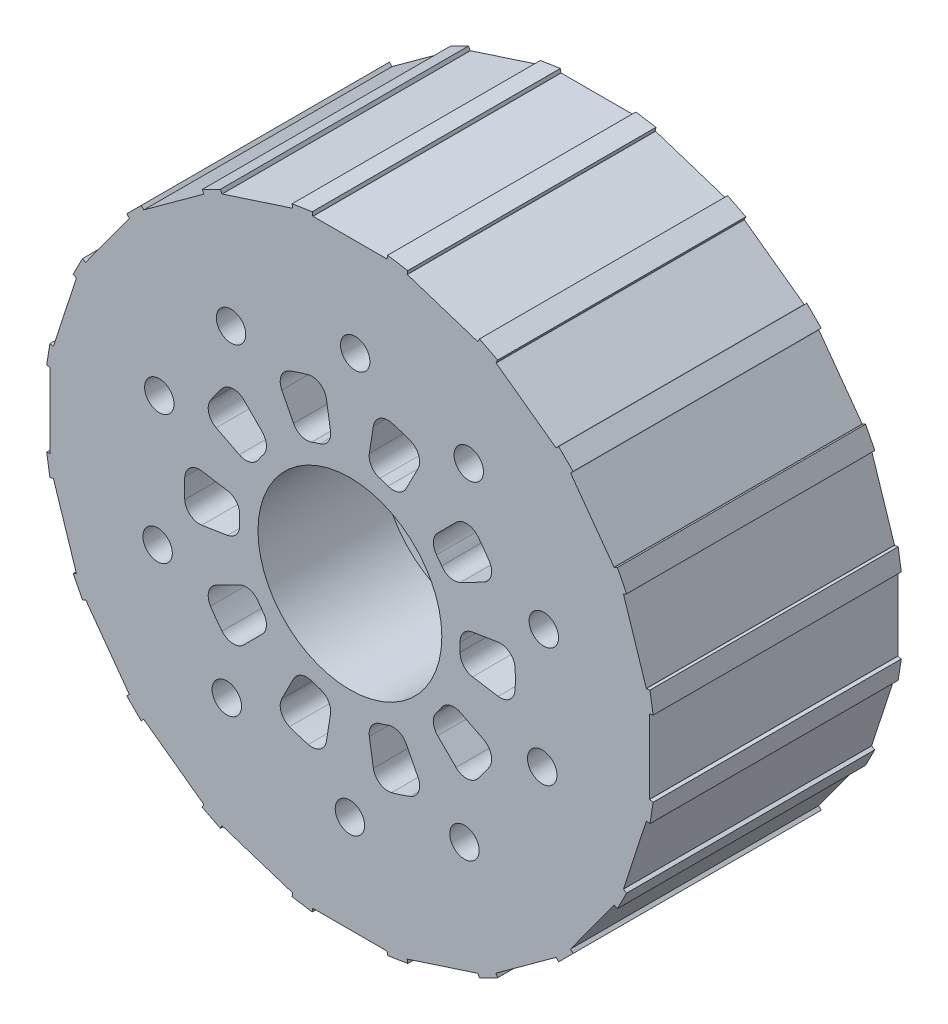
SolidWorks part; units mm, degrees
ref_plane "Ön Düzlem" through (0, 0, 0) normal (0, 0, 1) x (1, 0, 0)
ref_plane "Üst Düzlem" through (0, 0, 0) normal (0, 1, 0) x (1, 0, 0)
ref_plane "Sağ Düzlem" through (0, 0, 0) normal (1, 0, 0) x (0, 0, -1)
sketch "Sketch1" plane through (0, 0, 0) normal (0, 0, 1) x (1, 0, 0)
  line L0 (0, 0) -> (0, 81.5)
  line L1 (10, 81.5) -> (-10, 81.5)
  line L2 (-10, 81.5) -> (-10, 87.5)
  line L3 (10, 81.5) -> (10, 87.5)
  line L4 (15.6743, 80.6013) -> (17.5284, 86.3076)
  line L5 (34.6955, 74.4209) -> (36.5496, 80.1273)
  line L6 (34.6955, 74.4209) -> (15.6743, 80.6013)
  line L7 (39.8143, 71.8127) -> (43.341, 76.6668)
  line L8 (55.9947, 60.057) -> (59.5214, 64.9111)
  line L9 (55.9947, 60.057) -> (39.8143, 71.8127)
  line L10 (60.057, 55.9947) -> (64.9111, 59.5214)
  line L11 (71.8127, 39.8143) -> (76.6668, 43.341)
  line L12 (71.8127, 39.8143) -> (60.057, 55.9947)
  line L13 (74.4209, 34.6955) -> (80.1273, 36.5496)
  line L14 (80.6013, 15.6743) -> (86.3076, 17.5284)
  line L15 (80.6013, 15.6743) -> (74.4209, 34.6955)
  line L16 (81.5, 10) -> (87.5, 10)
  line L17 (81.5, -10) -> (87.5, -10)
  line L18 (81.5, -10) -> (81.5, 10)
  line L19 (80.6013, -15.6743) -> (86.3076, -17.5284)
  line L20 (74.4209, -34.6955) -> (80.1273, -36.5496)
  line L21 (74.4209, -34.6955) -> (80.6013, -15.6743)
  line L22 (71.8127, -39.8143) -> (76.6668, -43.341)
  line L23 (60.057, -55.9947) -> (64.9111, -59.5214)
  line L24 (60.057, -55.9947) -> (71.8127, -39.8143)
  line L25 (55.9947, -60.057) -> (59.5214, -64.9111)
  line L26 (39.8143, -71.8127) -> (43.341, -76.6668)
  line L27 (39.8143, -71.8127) -> (55.9947, -60.057)
  line L28 (34.6955, -74.4209) -> (36.5496, -80.1273)
  line L29 (15.6743, -80.6013) -> (17.5284, -86.3076)
  line L30 (15.6743, -80.6013) -> (34.6955, -74.4209)
  line L31 (10, -81.5) -> (10, -87.5)
  line L32 (-10, -81.5) -> (-10, -87.5)
  line L33 (-10, -81.5) -> (10, -81.5)
  line L34 (-15.6743, -80.6013) -> (-17.5284, -86.3076)
  line L35 (-34.6955, -74.4209) -> (-36.5496, -80.1273)
  line L36 (-34.6955, -74.4209) -> (-15.6743, -80.6013)
  line L37 (-39.8143, -71.8127) -> (-43.341, -76.6668)
  line L38 (-55.9947, -60.057) -> (-59.5214, -64.9111)
  line L39 (-55.9947, -60.057) -> (-39.8143, -71.8127)
  line L40 (-60.057, -55.9947) -> (-64.9111, -59.5214)
  line L41 (-71.8127, -39.8143) -> (-76.6668, -43.341)
  line L42 (-71.8127, -39.8143) -> (-60.057, -55.9947)
  line L43 (-74.4209, -34.6955) -> (-80.1273, -36.5496)
  line L44 (-80.6013, -15.6743) -> (-86.3076, -17.5284)
  line L45 (-80.6013, -15.6743) -> (-74.4209, -34.6955)
  line L46 (-81.5, -10) -> (-87.5, -10)
  line L47 (-81.5, 10) -> (-87.5, 10)
  line L48 (-81.5, 10) -> (-81.5, -10)
  line L49 (-80.6013, 15.6743) -> (-86.3076, 17.5284)
  line L50 (-74.4209, 34.6955) -> (-80.1273, 36.5496)
  line L51 (-74.4209, 34.6955) -> (-80.6013, 15.6743)
  line L52 (-71.8127, 39.8143) -> (-76.6668, 43.341)
  line L53 (-60.057, 55.9947) -> (-64.9111, 59.5214)
  line L54 (-60.057, 55.9947) -> (-71.8127, 39.8143)
  line L55 (-55.9947, 60.057) -> (-59.5214, 64.9111)
  line L56 (-39.8143, 71.8127) -> (-43.341, 76.6668)
  line L57 (-39.8143, 71.8127) -> (-55.9947, 60.057)
  line L58 (-34.6955, 74.4209) -> (-36.5496, 80.1273)
  line L59 (-15.6743, 80.6013) -> (-17.5284, 86.3076)
  line L60 (-15.6743, 80.6013) -> (-34.6955, 74.4209)
  line L61 (34.6955, 74.4209) -> (34.7846, 74.3755)
  line L62 (35.1494, 75.3119) -> (40.2683, 72.7037) construction
  line L63 (39.7252, 71.8581) -> (39.8143, 71.8127)
  line L64 (35.2385, 75.2665) -> (40.1792, 72.7491)
  line L65 (34.7846, 74.3755) -> (35.2385, 75.2665)
  line L66 (55.9947, 60.057) -> (56.0654, 59.9863)
  line L67 (39.7252, 71.8581) -> (40.1792, 72.7491)
  line L68 (34.7846, 74.3755) -> (35.1931, 75.1774) construction
  line L69 (39.7252, 71.8581) -> (40.1338, 72.66) construction
  line L70 (35.1931, 75.1774) -> (40.1338, 72.66) construction
  line L71 (34.6955, 74.4209) -> (35.1494, 75.3119) construction
  line L72 (39.8143, 71.8127) -> (40.2683, 72.7037) construction
  line L73 (56.0654, 59.9863) -> (56.7725, 60.6934)
  line L74 (56.7725, 60.6934) -> (60.6934, 56.7725)
  line L75 (59.9863, 56.0654) -> (60.6934, 56.7725)
  line L76 (59.9863, 56.0654) -> (60.057, 55.9947)
  line L77 (71.8127, 39.8143) -> (71.8581, 39.7252)
  line L78 (71.8581, 39.7252) -> (72.7491, 40.1792)
  line L79 (72.7491, 40.1792) -> (75.2665, 35.2385)
  line L80 (74.3755, 34.7846) -> (75.2665, 35.2385)
  line L81 (74.3755, 34.7846) -> (74.4209, 34.6955)
  line L82 (80.6013, 15.6743) -> (80.6169, 15.5756)
  line L83 (80.6169, 15.5756) -> (81.6046, 15.732)
  line L84 (81.6046, 15.732) -> (82.472, 10.2552)
  line L85 (81.4844, 10.0988) -> (82.472, 10.2552)
  line L86 (81.4844, 10.0988) -> (81.5, 10)
  line L87 (81.5, -10) -> (81.4844, -10.0988)
  line L88 (81.4844, -10.0988) -> (82.472, -10.2552)
  line L89 (82.472, -10.2552) -> (81.6046, -15.732)
  line L90 (80.6169, -15.5756) -> (81.6046, -15.732)
  line L91 (80.6169, -15.5756) -> (80.6013, -15.6743)
  line L92 (74.4209, -34.6955) -> (74.3755, -34.7846)
  line L93 (74.3755, -34.7846) -> (75.2665, -35.2385)
  line L94 (75.2665, -35.2385) -> (72.7491, -40.1792)
  line L95 (71.8581, -39.7252) -> (72.7491, -40.1792)
  line L96 (71.8581, -39.7252) -> (71.8127, -39.8143)
  line L97 (60.057, -55.9947) -> (59.9863, -56.0654)
  line L98 (59.9863, -56.0654) -> (60.6934, -56.7725)
  line L99 (60.6934, -56.7725) -> (56.7725, -60.6934)
  line L100 (56.0654, -59.9863) -> (56.7725, -60.6934)
  line L101 (56.0654, -59.9863) -> (55.9947, -60.057)
  line L102 (39.8143, -71.8127) -> (39.7252, -71.8581)
  line L103 (39.7252, -71.8581) -> (40.1792, -72.7491)
  line L104 (40.1792, -72.7491) -> (35.2385, -75.2665)
  line L105 (34.7846, -74.3755) -> (35.2385, -75.2665)
  line L106 (34.7846, -74.3755) -> (34.6955, -74.4209)
  line L107 (15.6743, -80.6013) -> (15.5756, -80.6169)
  line L108 (15.5756, -80.6169) -> (15.732, -81.6046)
  line L109 (15.732, -81.6046) -> (10.2552, -82.472)
  line L110 (10.0988, -81.4844) -> (10.2552, -82.472)
  line L111 (10.0988, -81.4844) -> (10, -81.5)
  line L112 (-10, -81.5) -> (-10.0988, -81.4844)
  line L113 (-10.0988, -81.4844) -> (-10.2552, -82.472)
  line L114 (-10.2552, -82.472) -> (-15.732, -81.6046)
  line L115 (-15.5756, -80.6169) -> (-15.732, -81.6046)
  line L116 (-15.5756, -80.6169) -> (-15.6743, -80.6013)
  line L117 (-34.6955, -74.4209) -> (-34.7846, -74.3755)
  line L118 (-34.7846, -74.3755) -> (-35.2385, -75.2665)
  line L119 (-35.2385, -75.2665) -> (-40.1792, -72.7491)
  line L120 (-39.7252, -71.8581) -> (-40.1792, -72.7491)
  line L121 (-39.7252, -71.8581) -> (-39.8143, -71.8127)
  line L122 (-55.9947, -60.057) -> (-56.0654, -59.9863)
  line L123 (-56.0654, -59.9863) -> (-56.7725, -60.6934)
  line L124 (-56.7725, -60.6934) -> (-60.6934, -56.7725)
  line L125 (-59.9863, -56.0654) -> (-60.6934, -56.7725)
  line L126 (-59.9863, -56.0654) -> (-60.057, -55.9947)
  line L127 (-71.8127, -39.8143) -> (-71.8581, -39.7252)
  line L128 (-71.8581, -39.7252) -> (-72.7491, -40.1792)
  line L129 (-72.7491, -40.1792) -> (-75.2665, -35.2385)
  line L130 (-74.3755, -34.7846) -> (-75.2665, -35.2385)
  line L131 (-74.3755, -34.7846) -> (-74.4209, -34.6955)
  line L132 (-80.6013, -15.6743) -> (-80.6169, -15.5756)
  line L133 (-80.6169, -15.5756) -> (-81.6046, -15.732)
  line L134 (-81.6046, -15.732) -> (-82.472, -10.2552)
  line L135 (-81.4844, -10.0988) -> (-82.472, -10.2552)
  line L136 (-81.4844, -10.0988) -> (-81.5, -10)
  line L137 (-81.5, 10) -> (-81.4844, 10.0988)
  line L138 (-81.4844, 10.0988) -> (-82.472, 10.2552)
  line L139 (-82.472, 10.2552) -> (-81.6046, 15.732)
  line L140 (-80.6169, 15.5756) -> (-81.6046, 15.732)
  line L141 (-80.6169, 15.5756) -> (-80.6013, 15.6743)
  line L142 (-74.4209, 34.6955) -> (-74.3755, 34.7846)
  line L143 (-74.3755, 34.7846) -> (-75.2665, 35.2385)
  line L144 (-75.2665, 35.2385) -> (-72.7491, 40.1792)
  line L145 (-71.8581, 39.7252) -> (-72.7491, 40.1792)
  line L146 (-71.8581, 39.7252) -> (-71.8127, 39.8143)
  line L147 (-60.057, 55.9947) -> (-59.9863, 56.0654)
  line L148 (-59.9863, 56.0654) -> (-60.6934, 56.7725)
  line L149 (-60.6934, 56.7725) -> (-56.7725, 60.6934)
  line L150 (-56.0654, 59.9863) -> (-56.7725, 60.6934)
  line L151 (-56.0654, 59.9863) -> (-55.9947, 60.057)
  line L152 (-39.8143, 71.8127) -> (-39.7252, 71.8581)
  line L153 (-39.7252, 71.8581) -> (-40.1792, 72.7491)
  line L154 (-40.1792, 72.7491) -> (-35.2385, 75.2665)
  line L155 (-34.7846, 74.3755) -> (-35.2385, 75.2665)
  line L156 (-34.7846, 74.3755) -> (-34.6955, 74.4209)
  line L157 (-15.6743, 80.6013) -> (-15.5756, 80.6169)
  line L158 (-15.5756, 80.6169) -> (-15.732, 81.6046)
  line L159 (-15.732, 81.6046) -> (-10.2552, 82.472)
  line L160 (-10.0988, 81.4844) -> (-10.2552, 82.472)
  line L161 (-10.0988, 81.4844) -> (-10, 81.5)
  line L162 (10, 81.5) -> (10.0988, 81.4844)
  line L163 (10.0988, 81.4844) -> (10.2552, 82.472)
  line L164 (10.2552, 82.472) -> (15.732, 81.6046)
  line L165 (15.5756, 80.6169) -> (15.732, 81.6046)
  line L166 (15.5756, 80.6169) -> (15.6743, 80.6013)
  circle A0 centre (0, 0) radius 25
  arc A2 (10, 87.5) -> (-10, 87.5) centre (0, 38) ccw
  arc A3 (36.5496, 80.1273) -> (17.5284, 86.3076) centre (11.7426, 36.1401) ccw
  arc A4 (59.5214, 64.9111) -> (43.341, 76.6668) centre (22.3358, 30.7426) ccw
  arc A5 (76.6668, 43.341) -> (64.9111, 59.5214) centre (30.7426, 22.3358) ccw
  arc A6 (86.3076, 17.5284) -> (80.1273, 36.5496) centre (36.1401, 11.7426) ccw
  arc A7 (87.5, -10) -> (87.5, 10) centre (38, 0) ccw
  arc A8 (80.1273, -36.5496) -> (86.3076, -17.5284) centre (36.1401, -11.7426) ccw
  arc A9 (64.9111, -59.5214) -> (76.6668, -43.341) centre (30.7426, -22.3358) ccw
  arc A10 (43.341, -76.6668) -> (59.5214, -64.9111) centre (22.3358, -30.7426) ccw
  arc A11 (17.5284, -86.3076) -> (36.5496, -80.1273) centre (11.7426, -36.1401) ccw
  arc A12 (-10, -87.5) -> (10, -87.5) centre (0, -38) ccw
  arc A13 (-36.5496, -80.1273) -> (-17.5284, -86.3076) centre (-11.7426, -36.1401) ccw
  arc A14 (-59.5214, -64.9111) -> (-43.341, -76.6668) centre (-22.3358, -30.7426) ccw
  arc A15 (-76.6668, -43.341) -> (-64.9111, -59.5214) centre (-30.7426, -22.3358) ccw
  arc A16 (-86.3076, -17.5284) -> (-80.1273, -36.5496) centre (-36.1401, -11.7426) ccw
  arc A17 (-87.5, 10) -> (-87.5, -10) centre (-38, 0) ccw
  arc A18 (-80.1273, 36.5496) -> (-86.3076, 17.5284) centre (-36.1401, 11.7426) ccw
  arc A19 (-64.9111, 59.5214) -> (-76.6668, 43.341) centre (-30.7426, 22.3358) ccw
  arc A20 (-43.341, 76.6668) -> (-59.5214, 64.9111) centre (-22.3358, 30.7426) ccw
  arc A21 (-17.5284, 86.3076) -> (-36.5496, 80.1273) centre (-11.7426, 36.1401) ccw
  point P7 (0, 81.5)
  point P107 (0, 0)
  point P231 (0, 0)
  dimension "D1" = 81.5
  dimension "D3" = 50.5
  dimension "D8" = 50
  dimension "D2" = 20
  dimension "D4" = 6
  dimension "D5" = 6
  dimension "D7" = 20
  dimension "D6" = 20
extrude "Boss-Extrude1" add sketch "Sketch1" along normal blind 67.5
sketch "Sketch2" plane through (0, 0, 0) normal (0, 0, -1) x (-1, 0, 0)
  circle A0 centre (0, 0) radius 68
extrude "Cut-Extrude1" cut sketch "Sketch2" against normal blind 33.75
sketch "Sketch3" plane through (0, 0, 33.75) normal (0, 0, -1) x (-1, 0, 0)
  line L0 (0, 0) -> (0, 55)
  line L1 (0, 0) -> (1.4397, 54.9812)
  circle A1 centre (32.3282, 44.4959) radius 4
  circle A3 centre (52.3081, -16.9959) radius 4
  circle A5 centre (0, -55) radius 4
  circle A7 centre (-52.3081, -16.9959) radius 4
  circle A9 centre (-32.3282, 44.4959) radius 4
  circle A11 centre (1.4397, 54.9812) radius 4
  circle A12 centre (52.7351, 15.6208) radius 4
  circle A13 centre (31.1523, -45.3269) radius 4
  circle A14 centre (-33.4819, -43.6344) radius 4
  circle A15 centre (-51.8453, 18.3594) radius 4
  point P24 (0, 0)
  point P28 (0, 0)
  point P37 (0, 0)
extrude "Cut-Extrude2" cut sketch "Sketch3" against normal blind 33.75
sketch "Sketch4" plane through (0, 0, 33.75) normal (0, 0, -1) x (-1, 0, 0)
  line L1 (-5.2818, 33.3482) -> (-6.3832, 40.302)
  line L2 (-15.3285, 30.0838) -> (-18.5248, 36.357)
  line L3 (15.3285, 30.0838) -> (18.5248, 36.357)
  line L4 (5.2818, 33.3482) -> (6.3832, 40.302)
  line L5 (30.0838, 15.3285) -> (36.357, 18.5248)
  line L6 (23.8747, 23.8747) -> (28.8531, 28.8531)
  line L7 (33.3482, -5.2818) -> (40.302, -6.3832)
  line L8 (33.3482, 5.2818) -> (40.302, 6.3832)
  line L9 (23.8747, -23.8747) -> (28.8531, -28.8531)
  line L10 (30.0838, -15.3285) -> (36.357, -18.5248)
  line L11 (5.2818, -33.3482) -> (6.3832, -40.302)
  line L12 (15.3285, -30.0838) -> (18.5248, -36.357)
  line L13 (-15.3285, -30.0838) -> (-18.5248, -36.357)
  line L14 (-5.2818, -33.3482) -> (-6.3832, -40.302)
  line L18 (-30.0838, 15.3285) -> (-36.357, 18.5248)
  line L19 (-23.8747, 23.8747) -> (-28.8531, 28.8531)
  line L24 (-30.0838, -15.3285) -> (-36.357, -18.5248)
  line L25 (-23.8747, -23.8747) -> (-28.8531, -28.8531)
  line L26 (-33.3482, 5.2818) -> (-40.302, 6.3832)
  line L27 (-33.3482, -5.2818) -> (-40.302, -6.3832)
  arc A0 (-34.7724, 28.5636) -> (-37.9109, 24.2439) centre (0, 0) ccw
  arc A1 (-23.5616, 18.5702) -> (-24.9422, 16.6699) centre (0, 0) ccw
  arc A6 (-37.9109, 24.2439) -> (-36.357, 18.5248) centre (-34.541, 22.0888) ccw
  arc A7 (-30.0838, 15.3285) -> (-24.9422, 16.6699) centre (-28.2679, 18.8925) ccw
  arc A8 (-23.5616, 18.5702) -> (-23.8747, 23.8747) centre (-26.7031, 21.0462) ccw
  arc A9 (-28.8531, 28.8531) -> (-34.7724, 28.5636) centre (-31.6815, 26.0246) ccw
  arc A10 (-6.3832, 40.302) -> (-11.3422, 43.5472) centre (-10.334, 39.6763) ccw
  arc A11 (-8.1464, 28.8728) -> (-5.2818, 33.3482) centre (-9.2326, 32.7225) ccw
  arc A12 (-11.3422, 43.5472) -> (-16.4204, 41.8971) centre (0, 0) ccw
  arc A13 (-16.4204, 41.8971) -> (-18.5248, 36.357) centre (-14.9608, 38.173) ccw
  arc A14 (-15.3285, 30.0838) -> (-10.3804, 28.1469) centre (-11.7645, 31.8998) ccw
  arc A15 (-8.1464, 28.8728) -> (-10.3804, 28.1469) centre (0, 0) ccw
  arc A16 (18.5248, 36.357) -> (16.4204, 41.8971) centre (14.9608, 38.173) ccw
  arc A17 (10.3804, 28.1469) -> (15.3285, 30.0838) centre (11.7645, 31.8998) ccw
  arc A18 (16.4204, 41.8971) -> (11.3422, 43.5472) centre (0, 0) ccw
  arc A19 (11.3422, 43.5472) -> (6.3832, 40.302) centre (10.334, 39.6763) ccw
  arc A20 (5.2818, 33.3482) -> (8.1464, 28.8728) centre (9.2326, 32.7225) ccw
  arc A21 (10.3804, 28.1469) -> (8.1464, 28.8728) centre (0, 0) ccw
  arc A22 (36.357, 18.5248) -> (37.9109, 24.2439) centre (34.541, 22.0888) ccw
  arc A23 (24.9422, 16.6699) -> (30.0838, 15.3285) centre (28.2679, 18.8925) ccw
  arc A24 (37.9109, 24.2439) -> (34.7724, 28.5636) centre (0, 0) ccw
  arc A25 (34.7724, 28.5636) -> (28.8531, 28.8531) centre (31.6815, 26.0246) ccw
  arc A26 (23.8747, 23.8747) -> (23.5616, 18.5702) centre (26.7031, 21.0462) ccw
  arc A27 (24.9422, 16.6699) -> (23.5616, 18.5702) centre (0, 0) ccw
  arc A28 (40.302, -6.3832) -> (44.9207, -2.6698) centre (40.9278, -2.4325) ccw
  arc A29 (29.977, -1.1745) -> (33.3482, -5.2818) centre (33.9739, -1.3311) ccw
  arc A30 (44.9207, -2.6698) -> (44.9207, 2.6698) centre (0, 0) ccw
  arc A31 (44.9207, 2.6698) -> (40.302, 6.3832) centre (40.9278, 2.4325) ccw
  arc A32 (33.3482, 5.2818) -> (29.977, 1.1745) centre (33.9739, 1.3311) ccw
  arc A33 (29.977, -1.1745) -> (29.977, 1.1745) centre (0, 0) ccw
  arc A34 (28.8531, -28.8531) -> (34.7724, -28.5636) centre (31.6815, -26.0246) ccw
  arc A35 (23.5616, -18.5702) -> (23.8747, -23.8747) centre (26.7031, -21.0462) ccw
  arc A36 (34.7724, -28.5636) -> (37.9109, -24.2439) centre (0, 0) ccw
  arc A37 (37.9109, -24.2439) -> (36.357, -18.5248) centre (34.541, -22.0888) ccw
  arc A38 (30.0838, -15.3285) -> (24.9422, -16.6699) centre (28.2679, -18.8925) ccw
  arc A39 (23.5616, -18.5702) -> (24.9422, -16.6699) centre (0, 0) ccw
  arc A40 (6.3832, -40.302) -> (11.3422, -43.5472) centre (10.334, -39.6763) ccw
  arc A41 (8.1464, -28.8728) -> (5.2818, -33.3482) centre (9.2326, -32.7225) ccw
  arc A42 (11.3422, -43.5472) -> (16.4204, -41.8971) centre (0, 0) ccw
  arc A43 (16.4204, -41.8971) -> (18.5248, -36.357) centre (14.9608, -38.173) ccw
  arc A44 (15.3285, -30.0838) -> (10.3804, -28.1469) centre (11.7645, -31.8998) ccw
  arc A45 (8.1464, -28.8728) -> (10.3804, -28.1469) centre (0, 0) ccw
  arc A46 (-18.5248, -36.357) -> (-16.4204, -41.8971) centre (-14.9608, -38.173) ccw
  arc A47 (-10.3804, -28.1469) -> (-15.3285, -30.0838) centre (-11.7645, -31.8998) ccw
  arc A48 (-16.4204, -41.8971) -> (-11.3422, -43.5472) centre (0, 0) ccw
  arc A49 (-11.3422, -43.5472) -> (-6.3832, -40.302) centre (-10.334, -39.6763) ccw
  arc A50 (-5.2818, -33.3482) -> (-8.1464, -28.8728) centre (-9.2326, -32.7225) ccw
  arc A51 (-10.3804, -28.1469) -> (-8.1464, -28.8728) centre (0, 0) ccw
  arc A52 (-36.357, -18.5248) -> (-37.9109, -24.2439) centre (-34.541, -22.0888) ccw
  arc A53 (-24.9422, -16.6699) -> (-30.0838, -15.3285) centre (-28.2679, -18.8925) ccw
  arc A54 (-37.9109, -24.2439) -> (-34.7724, -28.5636) centre (0, 0) ccw
  arc A55 (-34.7724, -28.5636) -> (-28.8531, -28.8531) centre (-31.6815, -26.0246) ccw
  arc A56 (-23.8747, -23.8747) -> (-23.5616, -18.5702) centre (-26.7031, -21.0462) ccw
  arc A57 (-24.9422, -16.6699) -> (-23.5616, -18.5702) centre (0, 0) ccw
  arc A58 (-40.302, 6.3832) -> (-44.9207, 2.6698) centre (-40.9278, 2.4325) ccw
  arc A59 (-29.977, 1.1745) -> (-33.3482, 5.2818) centre (-33.9739, 1.3311) ccw
  arc A60 (-44.9207, 2.6698) -> (-44.9207, -2.6698) centre (0, 0) ccw
  arc A61 (-44.9207, -2.6698) -> (-40.302, -6.3832) centre (-40.9278, -2.4325) ccw
  arc A62 (-33.3482, -5.2818) -> (-29.977, -1.1745) centre (-33.9739, -1.3311) ccw
  arc A63 (-29.977, 1.1745) -> (-29.977, -1.1745) centre (0, 0) ccw
  point P132 (0, 0)
  dimension "D1" = 4
extrude "Cut-Extrude3" cut sketch "Sketch4" against normal blind 33.75
sketch "Sketch5" plane through (0, 0, 33.75) normal (0, 0, -1) x (-1, 0, 0)
  line L0 (0, 0) -> (-1.4397, 54.9812)
  circle A0 centre (-1.4397, 54.9812) radius 4
  circle A1 centre (51.8453, 18.3594) radius 4
  circle A2 centre (33.4819, -43.6344) radius 4
  circle A3 centre (-31.1523, -45.3269) radius 4
  circle A4 centre (-52.7351, 15.6208) radius 4
  point P14 (0, 0)
extrude "Cut-Extrude4" cut sketch "Sketch5" against normal through all contours A4 | A0 | A1 | A2 | A3
